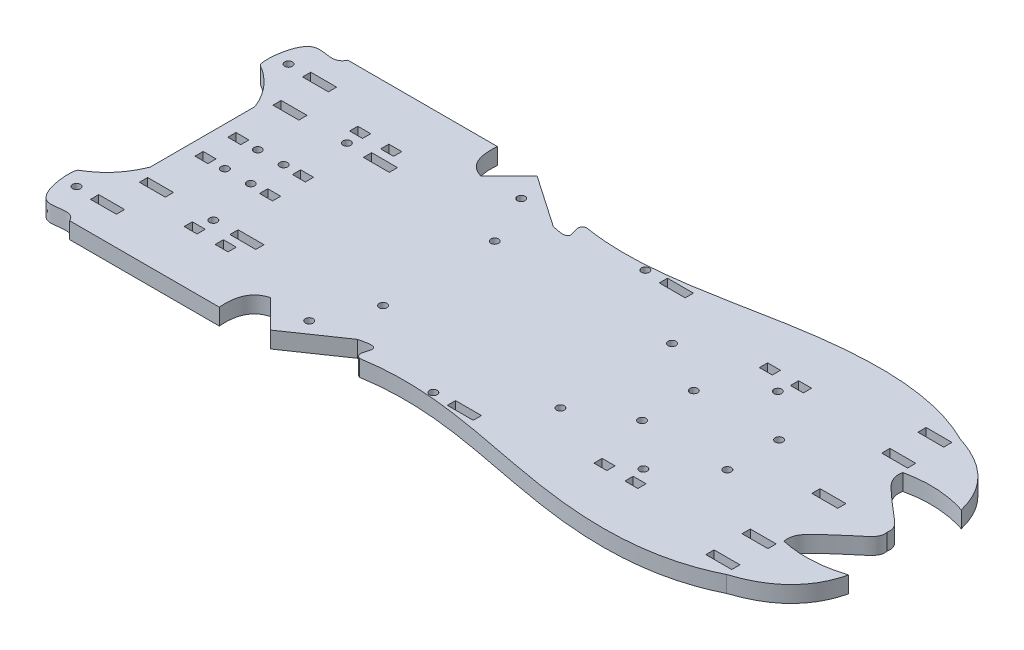
SolidWorks part; units mm, degrees
ref_plane "前视基准面" through (0, 0, 0) normal (0, 0, 1) x (1, 0, 0)
ref_plane "上视基准面" through (0, 0, 0) normal (0, 1, 0) x (1, 0, 0)
ref_plane "右视基准面" through (0, 0, 0) normal (1, 0, 0) x (0, 0, -1)
sketch "Sketch1" plane through (0, 0, 0) normal (0, 1, 0) x (1, 0, 0)
  line L0 (10.5269, -62.8027) -> (453.7588, -62.8027) construction
  line L1 (149.2972, 0) -> (-128.7028, 0) construction
  line L2 (-184.4845, 9.4891) -> (83.5155, 9.4891) construction
  dimension "D1" = 278
sketch "Sketch2" plane through (0, 0, 0) normal (0, 1, 0) x (1, 0, 0)
  line L0 (-170.8604, 0) -> (166.3868, 0) construction
  line L1 (-63.8404, 53.7851) -> (-121.7032, 53.7851)
  line L2 (-124.1047, 20.2534) -> (-124.1047, -20.2534)
  line L3 (-63.8404, -53.7851) -> (-121.7032, -53.7851)
  spline S0 degree 3 poles (140.662, 0) (141.3872, 2.7611) (135.7365, 7.3542) (128.6934, 13.5063) (122.9355, 18.9325) (123.7573, 22.9914) knots 0 0 0 0 0.249977 0.654822 1 1 1 1
  spline S1 degree 2 poles (123.7573, 22.9914) (135.6661, 25.6419) (147.5593, 21.7995) knots 0 0 0 1 1 1
  spline S2 degree 2 poles (147.5593, 21.7995) (143.4728, 38.9852) (123.7573, 45.2702) knots 0 0 0 1 1 1
  spline S3 degree 3 poles (123.7573, 45.2702) (104.0876, 55.1301) (53.5469, 54.4384) (7.187, 39.3743) (-19.5545, 43.8388) knots 0 0 0 0 0.449955 1 1 1 1
  spline S4 degree 3 poles (-19.5545, 43.8388) (-24.3449, 42.1677) (-14.2503, 34.7826) (-26.262, 37.8236) knots 0 0 0 0 1 1 1 1
  spline S5 degree 1 poles (-26.262, 37.8236) (-46.3096, 51.5978) knots 0 0 1 1
  spline S6 degree 1 poles (-46.3096, 51.5978) (-57.1158, 40.6993) knots 0 0 1 1
  spline S7 degree 2 poles (-57.1158, 40.6993) (-64.808, 42.8132) (-63.8404, 53.7851) knots 0 0 0 1 1 1
  spline S8 degree 3 poles (-121.7032, 53.7851) (-123.8199, 49.2101) (-137.2417, 58.4235) (-138.2637, 36.4234) (-136.9986, 35.2212) knots 0 0 0 0 0.398286 1 1 1 1
  spline S9 degree 2 poles (-136.9986, 35.2212) (-127.8855, 29.9113) (-124.1047, 20.2534) knots 0 0 0 1 1 1
  spline S10 degree 2 poles (-136.9986, -35.2212) (-127.8855, -29.9113) (-124.1047, -20.2534) knots 0 0 0 1 1 1
  spline S11 degree 3 poles (-121.7032, -53.7851) (-123.8199, -49.2101) (-137.2417, -58.4235) (-138.2637, -36.4234) (-136.9986, -35.2212) knots 0 0 0 0 0.398286 1 1 1 1
  spline S12 degree 2 poles (-57.1158, -40.6993) (-64.808, -42.8132) (-63.8404, -53.7851) knots 0 0 0 1 1 1
  spline S13 degree 1 poles (-46.3096, -51.5978) (-57.1158, -40.6993) knots 0 0 1 1
  spline S14 degree 1 poles (-26.262, -37.8236) (-46.3096, -51.5978) knots 0 0 1 1
  spline S15 degree 3 poles (-19.5545, -43.8388) (-24.3449, -42.1677) (-14.2503, -34.7826) (-26.262, -37.8236) knots 0 0 0 0 1 1 1 1
  spline S16 degree 3 poles (123.7573, -45.2702) (104.0876, -55.1301) (53.5469, -54.4384) (7.187, -39.3743) (-19.5545, -43.8388) knots 0 0 0 0 0.449955 1 1 1 1
  spline S17 degree 2 poles (147.5593, -21.7995) (143.4728, -38.9852) (123.7573, -45.2702) knots 0 0 0 1 1 1
  spline S18 degree 2 poles (123.7573, -22.9914) (135.6661, -25.6419) (147.5593, -21.7995) knots 0 0 0 1 1 1
  spline S19 degree 3 poles (140.662, 0) (141.3872, -2.7611) (135.7365, -7.3542) (128.6934, -13.5063) (122.9355, -18.9325) (123.7573, -22.9914) knots 0 0 0 0 0.249977 0.654822 1 1 1 1
  point P59 (-124.1047, 0)
extrude "Boss-Extrude1" add sketch "Sketch2" along normal blind 6.35
sketch "Sketch3" plane through (0, 6.35, 0) normal (0, 1, 0) x (1, 0, 0)
  line L0 (-136.5043, 0) -> (151.5478, 0) construction
  line L1 (172.4729, 41) -> (-148.1908, 41) construction
  line L2 (68.1603, 64.0219) -> (68.1603, 18.9749) construction
  line L3 (123.1603, 42.5875) -> (113.1603, 42.5875)
  line L4 (123.1603, 42.5875) -> (123.1603, 39.4125)
  line L5 (123.1603, 39.4125) -> (113.1603, 39.4125)
  line L6 (113.1603, 42.5875) -> (113.1603, 39.4125)
  line L7 (123.1603, 42.5875) -> (113.1603, 39.4125) construction
  line L8 (123.1603, 39.4125) -> (113.1603, 42.5875) construction
  line L9 (13.1603, 39.4125) -> (23.1603, 42.5875) construction
  line L10 (13.1603, 42.5875) -> (23.1603, 39.4125) construction
  line L11 (23.1603, 42.5875) -> (23.1603, 39.4125)
  line L12 (13.1603, 39.4125) -> (23.1603, 39.4125)
  line L13 (13.1603, 42.5875) -> (13.1603, 39.4125)
  line L14 (13.1603, 42.5875) -> (23.1603, 42.5875)
  line L15 (-0.8397, 68.81) -> (-0.8397, 15.386) construction
  line L16 (-124.8397, 39.4125) -> (-114.8397, 42.5875) construction
  line L17 (-124.8397, 42.5875) -> (-114.8397, 39.4125) construction
  line L18 (-114.8397, 42.5875) -> (-114.8397, 39.4125)
  line L19 (-124.8397, 39.4125) -> (-114.8397, 39.4125)
  line L20 (-124.8397, 42.5875) -> (-124.8397, 39.4125)
  line L21 (-124.8397, 42.5875) -> (-114.8397, 42.5875)
  line L22 (-124.8397, -42.5875) -> (-114.8397, -39.4125) construction
  line L23 (-124.8397, -39.4125) -> (-114.8397, -42.5875) construction
  line L24 (13.1603, -42.5875) -> (23.1603, -39.4125) construction
  line L25 (13.1603, -39.4125) -> (23.1603, -42.5875) construction
  line L26 (123.1603, -39.4125) -> (113.1603, -42.5875) construction
  line L27 (123.1603, -42.5875) -> (113.1603, -39.4125) construction
  line L28 (-124.8397, -42.5875) -> (-114.8397, -42.5875)
  line L29 (-124.8397, -42.5875) -> (-124.8397, -39.4125)
  line L30 (-124.8397, -39.4125) -> (-114.8397, -39.4125)
  line L31 (-114.8397, -42.5875) -> (-114.8397, -39.4125)
  line L32 (13.1603, -42.5875) -> (23.1603, -42.5875)
  line L33 (13.1603, -42.5875) -> (13.1603, -39.4125)
  line L34 (13.1603, -39.4125) -> (23.1603, -39.4125)
  line L35 (23.1603, -42.5875) -> (23.1603, -39.4125)
  line L36 (113.1603, -42.5875) -> (113.1603, -39.4125)
  line L37 (123.1603, -39.4125) -> (113.1603, -39.4125)
  line L38 (123.1603, -42.5875) -> (123.1603, -39.4125)
  line L39 (123.1603, -42.5875) -> (113.1603, -42.5875)
  line L40 (118.1603, 59.1499) -> (118.1603, -18.3287) construction
  line L41 (123.1603, 1.5875) -> (113.1603, 1.5875)
  line L42 (123.1603, -1.5875) -> (113.1603, -1.5875)
  line L43 (123.1603, -1.5875) -> (113.1603, 1.5875) construction
  line L44 (123.1603, 1.5875) -> (123.1603, -1.5875)
  line L45 (123.1603, 1.5875) -> (113.1603, -1.5875) construction
  line L46 (113.1603, 1.5875) -> (113.1603, -1.5875)
  line L47 (123.1603, 28.5875) -> (113.1603, 28.5875)
  line L48 (123.1603, 25.4125) -> (113.1603, 25.4125)
  line L49 (123.1603, 28.5875) -> (123.1603, 25.4125)
  line L50 (113.1603, 28.5875) -> (113.1603, 25.4125)
  line L51 (123.1603, 25.4125) -> (113.1603, 28.5875) construction
  line L52 (123.1603, 28.5875) -> (113.1603, 25.4125) construction
  line L53 (123.1603, -25.4125) -> (113.1603, -25.4125)
  line L54 (123.1603, -28.5875) -> (113.1603, -25.4125) construction
  line L55 (123.1603, -28.5875) -> (123.1603, -25.4125)
  line L56 (123.1603, -25.4125) -> (113.1603, -28.5875) construction
  line L57 (113.1603, -28.5875) -> (113.1603, -25.4125)
  line L58 (123.1603, -28.5875) -> (113.1603, -28.5875)
  circle A0 centre (6.1603, 41) radius 1.5
  circle A1 centre (-41.8397, 41) radius 1.5
  circle A2 centre (-131.8397, 41) radius 1.5
  circle A3 centre (6.1603, -41) radius 1.5
  circle A4 centre (-41.8397, -41) radius 1.5
  circle A5 centre (-131.8397, -41) radius 1.5
  point P5 (118.1603, 41)
  point P10 (133.1603, 41)
  point P17 (18.1603, 41)
  point P24 (-119.8397, 41)
  point P37 (-119.8397, -41)
  point P38 (18.1603, -41)
  point P39 (118.1603, -41)
  point P54 (118.1603, 0)
  point P60 (118.1603, 27)
  dimension "D8" = 3
  dimension "D9" = 3
  dimension "D11" = 3
  dimension "D1" = 41
  dimension "D2" = 10
  dimension "D3" = 3.175
  dimension "D4" = 15
  dimension "D5" = 100
  dimension "D6" = 238
  dimension "D7" = 117
  dimension "D10" = 165
  dimension "D12" = 255
  dimension "D13" = 10
  dimension "D14" = 3.175
  dimension "D16" = 27
  dimension "D15" = 2
extrude "Cut-Extrude1" cut sketch "Sketch3" against normal through all
sketch "Sketch5" plane through (0, 6.35, 0) normal (0, 1, 0) x (1, 0, 0)
  line L0 (-137.8228, 0) -> (156.6911, 0) construction
  line L1 (69.3603, 63.44) -> (69.3603, -23.9466) construction
  line L3 (-89.1347, 32) -> (69.3603, 32) construction
  line L5 (72.8603, 33.5875) -> (77.8603, 30.4125) construction
  line L6 (65.8603, 30.4125) -> (60.8603, 30.4125)
  line L7 (65.8603, 30.4125) -> (65.8603, 33.5875)
  line L8 (65.8603, 33.5875) -> (60.8603, 33.5875)
  line L9 (60.8603, 30.4125) -> (60.8603, 33.5875)
  line L10 (65.8603, 30.4125) -> (60.8603, 33.5875) construction
  line L11 (65.8603, 33.5875) -> (60.8603, 30.4125) construction
  line L12 (72.8603, 30.4125) -> (77.8603, 33.5875) construction
  line L13 (77.8603, 30.4125) -> (77.8603, 33.5875)
  line L14 (72.8603, 33.5875) -> (77.8603, 33.5875)
  line L15 (72.8603, 30.4125) -> (72.8603, 33.5875)
  line L16 (72.8603, 30.4125) -> (77.8603, 30.4125)
  line L17 (-89.1347, 47.3689) -> (-89.1347, -19.032) construction
  line L18 (-124.1047, 20.2534) -> (-124.1047, -20.2534) construction
  line L19 (-9.8872, 32) -> (-9.8872, 71.4552) construction
  line L20 (-92.6347, 30.4125) -> (-97.6347, 33.5875) construction
  line L21 (-85.6347, 33.5875) -> (-80.6347, 30.4125) construction
  line L22 (-85.6347, 30.4125) -> (-80.6347, 33.5875) construction
  line L23 (-92.6347, 33.5875) -> (-97.6347, 30.4125) construction
  line L24 (-92.6347, 30.4125) -> (-97.6347, 30.4125)
  line L25 (-92.6347, 30.4125) -> (-92.6347, 33.5875)
  line L26 (-92.6347, 33.5875) -> (-97.6347, 33.5875)
  line L27 (-97.6347, 30.4125) -> (-97.6347, 33.5875)
  line L28 (-80.6347, 30.4125) -> (-80.6347, 33.5875)
  line L29 (-85.6347, 33.5875) -> (-80.6347, 33.5875)
  line L30 (-85.6347, 30.4125) -> (-85.6347, 33.5875)
  line L31 (-85.6347, 30.4125) -> (-80.6347, 30.4125)
  line L32 (72.8603, -30.4125) -> (77.8603, -33.5875) construction
  line L33 (65.8603, -33.5875) -> (60.8603, -30.4125) construction
  line L34 (65.8603, -30.4125) -> (60.8603, -33.5875) construction
  line L35 (72.8603, -33.5875) -> (77.8603, -30.4125) construction
  line L36 (72.8603, -30.4125) -> (77.8603, -30.4125)
  line L37 (72.8603, -30.4125) -> (72.8603, -33.5875)
  line L38 (72.8603, -33.5875) -> (77.8603, -33.5875)
  line L39 (77.8603, -30.4125) -> (77.8603, -33.5875)
  line L40 (60.8603, -30.4125) -> (60.8603, -33.5875)
  line L41 (65.8603, -33.5875) -> (60.8603, -33.5875)
  line L42 (65.8603, -30.4125) -> (65.8603, -33.5875)
  line L43 (65.8603, -30.4125) -> (60.8603, -30.4125)
  line L44 (-92.6347, -33.5875) -> (-97.6347, -30.4125) construction
  line L45 (-85.6347, -30.4125) -> (-80.6347, -33.5875) construction
  line L46 (-85.6347, -33.5875) -> (-80.6347, -30.4125) construction
  line L47 (-92.6347, -30.4125) -> (-97.6347, -33.5875) construction
  line L48 (-85.6347, -30.4125) -> (-80.6347, -30.4125)
  line L49 (-85.6347, -30.4125) -> (-85.6347, -33.5875)
  line L50 (-85.6347, -33.5875) -> (-80.6347, -33.5875)
  line L51 (-80.6347, -30.4125) -> (-80.6347, -33.5875)
  line L52 (-97.6347, -30.4125) -> (-97.6347, -33.5875)
  line L53 (-92.6347, -33.5875) -> (-97.6347, -33.5875)
  line L54 (-92.6347, -30.4125) -> (-92.6347, -33.5875)
  line L55 (-92.6347, -30.4125) -> (-97.6347, -30.4125)
  point P11 (63.3603, 32)
  point P20 (75.3603, 32)
  point P31 (-95.1347, 32)
  point P32 (-83.1347, 32)
  point P41 (75.3603, -32)
  point P42 (63.3603, -32)
  point P51 (-83.1347, -32)
  point P52 (-95.1347, -32)
  dimension "D1" = 193.465
  dimension "D2" = 32
  dimension "D3" = 3.175
  dimension "D4" = 5
  dimension "D5" = 12
  dimension "D6" = 34.97
extrude "Cut-Extrude2" cut sketch "Sketch5" against normal through all
sketch "Sketch6" plane through (0, 6.35, 0) normal (0, 1, 0) x (1, 0, 0)
  line L0 (0, 0) -> (-67.1181, 0) construction
  line L1 (55.8953, 18.4804) -> (55.8953, -19.3911) construction
  line L2 (-124.1047, 20.2534) -> (-124.1047, -20.2534) construction
  line L3 (72.3953, 10) -> (72.3953, 23.5486) construction
  line L4 (55.8953, 10) -> (88.8953, 10) construction
  line L5 (1.6053, 18.4804) -> (1.6053, -20.559) construction
  circle A0 centre (55.8953, 10) radius 1.5
  circle A1 centre (88.8953, 10) radius 1.5
  circle A2 centre (72.3953, 26) radius 1.5
  circle A3 centre (88.8953, -10) radius 1.5
  circle A4 centre (55.8953, -10) radius 1.5
  circle A5 centre (72.3953, -26) radius 1.5
  circle A6 centre (35.8953, 21.59) radius 1.5
  circle A7 centre (35.8953, -21.59) radius 1.5
  circle A8 centre (-32.6847, -21.59) radius 1.5
  circle A9 centre (-32.6847, 21.59) radius 1.5
  dimension "D1" = 3
  dimension "D3" = 3
  dimension "D5" = 3
  dimension "D8" = 3
  dimension "D2" = 180
  dimension "D4" = 33
  dimension "D6" = 20
  dimension "D7" = 52
  dimension "D9" = 68.58
  dimension "D10" = 43.18
  dimension "D11" = 20
extrude "Cut-Extrude3" cut sketch "Sketch6" against normal through all
sketch "Sketch7" plane through (0, 6.35, 0) normal (0, 1, 0) x (1, 0, 0)
  line L0 (0, 0) -> (-134.4635, 0) construction
  line L1 (-116.1047, 29.0267) -> (-116.1047, -8.1812) construction
  line L2 (-124.1047, 20.2534) -> (-124.1047, -20.2534) construction
  line L3 (-111.1047, 24.2375) -> (-121.1047, 24.2375)
  line L4 (-111.1047, 24.2375) -> (-111.1047, 27.4125)
  line L5 (-111.1047, 27.4125) -> (-121.1047, 27.4125)
  line L6 (-121.1047, 24.2375) -> (-121.1047, 27.4125)
  line L7 (-111.1047, 24.2375) -> (-121.1047, 27.4125) construction
  line L8 (-111.1047, 27.4125) -> (-121.1047, 24.2375) construction
  line L9 (-97.6347, 30.4125) -> (-92.6347, 30.4125) construction
  line L10 (-98.6047, 25.825) -> (-98.6047, 10.3174) construction
  line L11 (-86.1047, 27.4125) -> (-76.1047, 24.2375) construction
  line L12 (-86.1047, 24.2375) -> (-76.1047, 27.4125) construction
  line L13 (-76.1047, 24.2375) -> (-76.1047, 27.4125)
  line L14 (-86.1047, 27.4125) -> (-76.1047, 27.4125)
  line L15 (-86.1047, 24.2375) -> (-86.1047, 27.4125)
  line L16 (-86.1047, 24.2375) -> (-76.1047, 24.2375)
  line L17 (-86.1047, -24.2375) -> (-76.1047, -27.4125) construction
  line L18 (-86.1047, -27.4125) -> (-76.1047, -24.2375) construction
  line L19 (-86.1047, -24.2375) -> (-76.1047, -24.2375)
  line L20 (-86.1047, -24.2375) -> (-86.1047, -27.4125)
  line L21 (-86.1047, -27.4125) -> (-76.1047, -27.4125)
  line L22 (-76.1047, -24.2375) -> (-76.1047, -27.4125)
  line L23 (-111.1047, -27.4125) -> (-121.1047, -24.2375) construction
  line L24 (-111.1047, -24.2375) -> (-121.1047, -27.4125) construction
  line L25 (-121.1047, -24.2375) -> (-121.1047, -27.4125)
  line L26 (-111.1047, -27.4125) -> (-121.1047, -27.4125)
  line L27 (-111.1047, -24.2375) -> (-111.1047, -27.4125)
  line L28 (-111.1047, -24.2375) -> (-121.1047, -24.2375)
  line L29 (-116.1047, 25.825) -> (-89.6698, 25.825) construction
  circle A0 centre (-94.1047, 25.825) radius 1.5
  circle A1 centre (-94.1047, -25.825) radius 1.5
  point P5 (-116.1047, 25.825)
  point P20 (-81.1047, 25.825)
  point P25 (-81.1047, -25.825)
  point P30 (-116.1047, -25.825)
  dimension "D6" = 3
  dimension "D1" = 3.175
  dimension "D2" = 10
  dimension "D3" = 8
  dimension "D4" = 3
  dimension "D5" = 25
  dimension "D7" = 8
extrude "Cut-Extrude4" cut sketch "Sketch7" against normal through all
sketch "Sketch8" plane through (0, 6.35, 0) normal (0, 1, 0) x (1, 0, 0)
  line L0 (0, 0) -> (-153.5755, 0) construction
  line L1 (-104.1047, 19.1747) -> (-104.1047, -20.3107) construction
  line L2 (-138.7268, 6.35) -> (-93.9689, 6.35) construction
  line L5 (-89.1047, 7.9375) -> (-94.1047, 4.7625) construction
  line L6 (-119.1047, 4.7625) -> (-114.1047, 4.7625)
  line L7 (-119.1047, 4.7625) -> (-119.1047, 7.9375)
  line L8 (-119.1047, 7.9375) -> (-114.1047, 7.9375)
  line L9 (-114.1047, 4.7625) -> (-114.1047, 7.9375)
  line L10 (-119.1047, 4.7625) -> (-114.1047, 7.9375) construction
  line L11 (-119.1047, 7.9375) -> (-114.1047, 4.7625) construction
  line L12 (-89.1047, 4.7625) -> (-94.1047, 7.9375) construction
  line L13 (-94.1047, 4.7625) -> (-94.1047, 7.9375)
  line L14 (-89.1047, 7.9375) -> (-94.1047, 7.9375)
  line L15 (-89.1047, 4.7625) -> (-89.1047, 7.9375)
  line L16 (-89.1047, 4.7625) -> (-94.1047, 4.7625)
  line L17 (-124.1047, 20.2534) -> (-124.1047, -20.2534) construction
  line L18 (-89.1047, -4.7625) -> (-94.1047, -7.9375) construction
  line L19 (-119.1047, -7.9375) -> (-114.1047, -4.7625) construction
  line L20 (-119.1047, -4.7625) -> (-114.1047, -7.9375) construction
  line L21 (-89.1047, -7.9375) -> (-94.1047, -4.7625) construction
  line L22 (-89.1047, -4.7625) -> (-94.1047, -4.7625)
  line L23 (-89.1047, -4.7625) -> (-89.1047, -7.9375)
  line L24 (-89.1047, -7.9375) -> (-94.1047, -7.9375)
  line L25 (-94.1047, -4.7625) -> (-94.1047, -7.9375)
  line L26 (-114.1047, -4.7625) -> (-114.1047, -7.9375)
  line L27 (-119.1047, -7.9375) -> (-114.1047, -7.9375)
  line L28 (-119.1047, -4.7625) -> (-119.1047, -7.9375)
  line L29 (-119.1047, -4.7625) -> (-114.1047, -4.7625)
  circle A0 centre (-109.1047, 6.35) radius 1.5
  circle A1 centre (-99.1047, 6.35) radius 1.5
  circle A2 centre (-99.1047, -6.35) radius 1.5
  circle A3 centre (-109.1047, -6.35) radius 1.5
  point P9 (-116.6047, 6.35)
  point P18 (-91.6047, 6.35)
  point P37 (-91.6047, -6.35)
  point P38 (-116.6047, -6.35)
  dimension "D6" = 3
  dimension "D1" = 12.7
  dimension "D2" = 3.175
  dimension "D3" = 5
  dimension "D4" = 25
  dimension "D5" = 5
  dimension "D7" = 10
extrude "Cut-Extrude5" cut sketch "Sketch8" against normal through all
